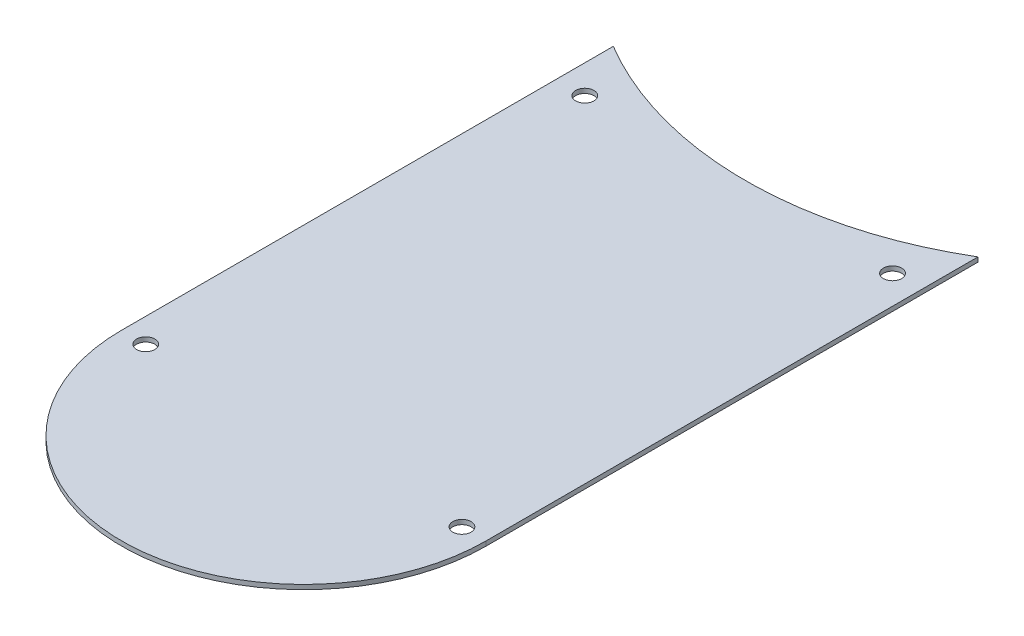
SolidWorks part; units mm, degrees
ref_plane "Front Plane" through (0, 0, 0) normal (0, 0, 1) x (1, 0, 0)
ref_plane "Top Plane" through (0, 0, 0) normal (0, 1, 0) x (1, 0, 0)
ref_plane "Right Plane" through (0, 0, 0) normal (1, 0, 0) x (0, 0, -1)
sketch "Sketch1" plane through (0, 0, 0) normal (0, 1, 0) x (1, 0, 0)
  line L0 (-32, -38.0313) -> (-32, 48.2822)
  line L1 (32, -38.0313) -> (32, 48.2822)
  arc A0 (-32, 48.2822) -> (32, 48.2822) centre (0, 101.9687) ccw
  arc A1 (-32, -38.0313) -> (32, -38.0313) centre (0, -38.0313) ccw
  arc A2 (-32, -38.0313) -> (32, -38.0313) centre (0, -38.0313) ccw construction
  arc A3 (-32, -38.0313) -> (32, -38.0313) centre (0, -38.0313) ccw construction
  arc A4 (32, 48.2822) -> (-32, 48.2822) centre (0, 101.9687) ccw construction
  arc A5 (32, 48.2822) -> (-32, 48.2822) centre (0, 101.9687) ccw construction
  dimension "D1" = 0
extrude "Boss-Extrude1" add sketch "Sketch1" along normal blind 0.8
sketch "Sketch2" plane through (0, 0, 0) normal (0, -1, 0) x (1, 0, 0)
  circle A0 centre (27.75, 38.0313) radius 1.6 construction
  circle A1 centre (-27.75, 38.0313) radius 1.6 construction
  circle A2 centre (27, -38.2822) radius 1.6 construction
  circle A3 centre (-27, -38.2822) radius 1.6 construction
  circle A4 centre (27.75, 38.0313) radius 1.6
  circle A5 centre (-27.75, 38.0313) radius 1.6
  circle A6 centre (27, -38.2822) radius 1.6
  circle A7 centre (-27, -38.2822) radius 1.6
extrude "Cut-Extrude1" cut sketch "Sketch2" against normal through all
